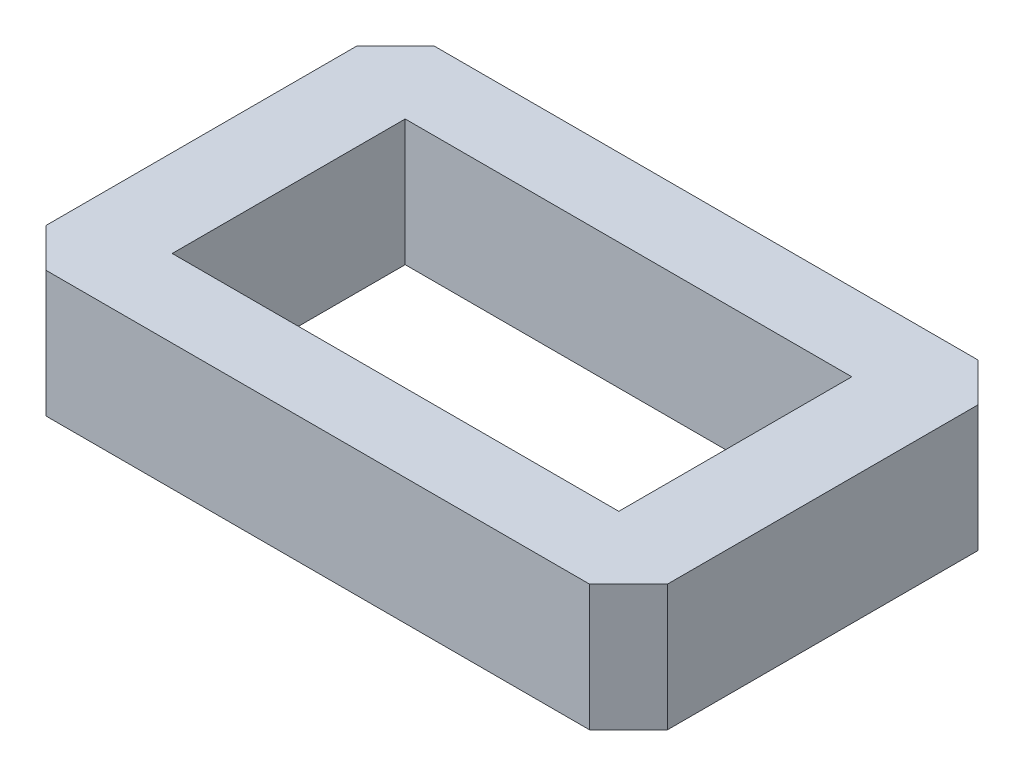
SolidWorks part; units mm, degrees
ref_plane "Front Plane" through (0, 0, 0) normal (0, 0, 1) x (1, 0, 0)
ref_plane "Top Plane" through (0, 0, 0) normal (0, 1, 0) x (1, 0, 0)
ref_plane "Right Plane" through (0, 0, 0) normal (1, 0, 0) x (0, 0, -1)
sketch "Sketch1" plane through (0, 0, 0) normal (0, 1, 0) x (1, 0, 0)
  line L1 (-16, -10) -> (16, -10)
  line L2 (-16, -10) -> (-16, 10)
  line L3 (-16, 10) -> (16, 10)
  line L4 (16, -10) -> (16, 10)
  line L5 (-16, -10) -> (16, 10) construction
  line L6 (-16, 10) -> (16, -10) construction
  point P0 (0, 0)
  dimension "D1" = 20
  dimension "D2" = 32
extrude "Boss-Extrude1" add sketch "Sketch1" along normal blind 6.5
sketch "Sketch2" plane through (0, 6.5, 0) normal (0, 1, 0) x (1, 0, 0)
  line L1 (-11.5, -6) -> (11.5, -6)
  line L2 (-11.5, -6) -> (-11.5, 6)
  line L3 (-11.5, 6) -> (11.5, 6)
  line L4 (11.5, -6) -> (11.5, 6)
  line L5 (-11.5, -6) -> (11.5, 6) construction
  line L6 (-11.5, 6) -> (11.5, -6) construction
  point P0 (0, 0)
  dimension "D1" = 12
  dimension "D2" = 23
extrude "Cut-Extrude1" cut sketch "Sketch2" against normal through all
chamfer "Chamfer1" distance 2 angle 45 4 edges at (-16, 3.25, -10) (16, 3.25, -10) (16, 3.25, 10) (-16, 3.25, 10)
